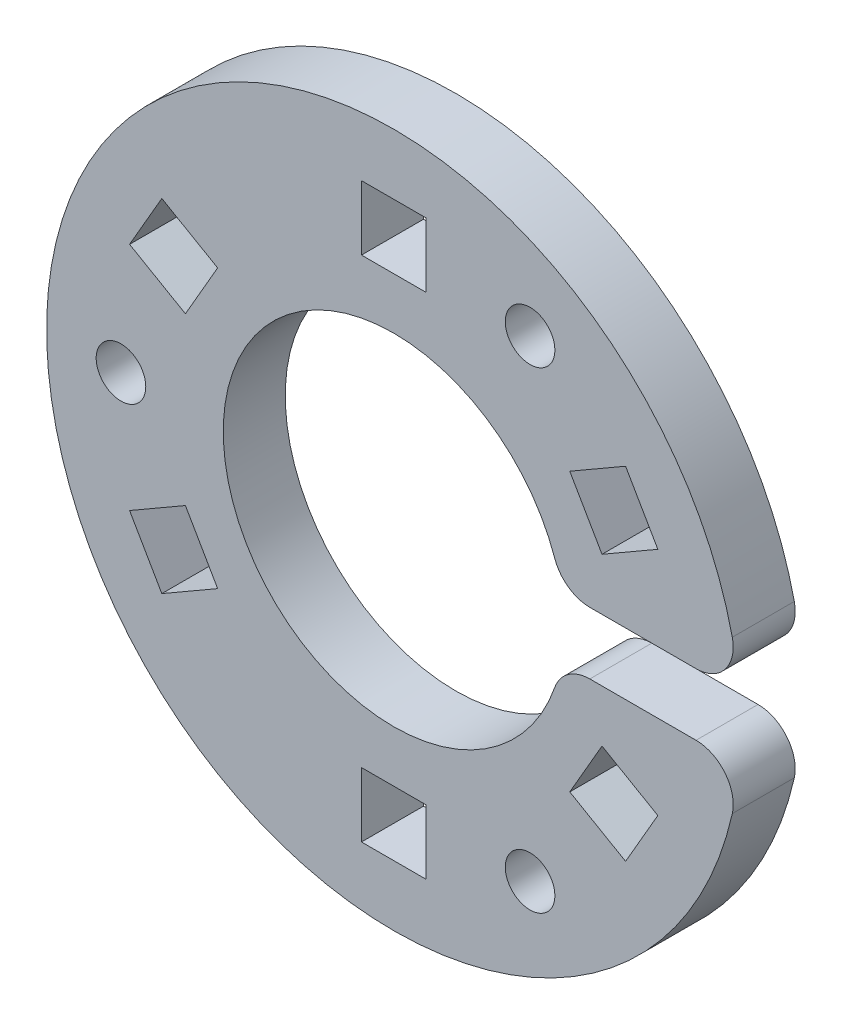
SolidWorks part; units mm, degrees
ref_plane "Front Plane" through (0, 0, 0) normal (0, 0, 1) x (1, 0, 0)
ref_plane "Top Plane" through (0, 0, 0) normal (0, 1, 0) x (1, 0, 0)
ref_plane "Right Plane" through (0, 0, 0) normal (1, 0, 0) x (0, 0, -1)
sketch "Sketch1" plane through (0, 0, 0) normal (0, 0, 1) x (1, 0, 0)
  line L0 (-26, 0) -> (26, 0) construction
  line L7 (-2.6, 23.1) -> (2.6, 23.1)
  line L8 (-2.6, 23.1) -> (-2.6, 17.9)
  line L9 (-2.6, 17.9) -> (2.6, 17.9)
  line L10 (2.6, 23.1) -> (2.6, 17.9)
  line L23 (0, 26) -> (0, -26) construction
  line L24 (21.3052, 9.2983) -> (16.8019, 6.6983)
  line L25 (14.2019, 11.2017) -> (16.8019, 6.6983)
  line L26 (18.7052, 13.8017) -> (14.2019, 11.2017)
  line L27 (18.7052, 13.8017) -> (21.3052, 9.2983)
  line L28 (18.7052, -13.8017) -> (14.2019, -11.2017)
  line L29 (16.8019, -6.6983) -> (14.2019, -11.2017)
  line L30 (21.3052, -9.2983) -> (16.8019, -6.6983)
  line L31 (21.3052, -9.2983) -> (18.7052, -13.8017)
  line L32 (-2.6, -23.1) -> (-2.6, -17.9)
  line L33 (2.6, -17.9) -> (-2.6, -17.9)
  line L34 (2.6, -23.1) -> (2.6, -17.9)
  line L35 (2.6, -23.1) -> (-2.6, -23.1)
  line L36 (-21.3052, -9.2983) -> (-16.8019, -6.6983)
  line L37 (-14.2019, -11.2017) -> (-16.8019, -6.6983)
  line L38 (-18.7052, -13.8017) -> (-14.2019, -11.2017)
  line L39 (-18.7052, -13.8017) -> (-21.3052, -9.2983)
  line L40 (-18.7052, 13.8017) -> (-14.2019, 11.2017)
  line L41 (-16.8019, 6.6983) -> (-14.2019, 11.2017)
  line L42 (-21.3052, 9.2983) -> (-16.8019, 6.6983)
  line L43 (-21.3052, 9.2983) -> (-18.7052, 13.8017)
  line L44 (27.8882, 2.5) -> (13.5208, 2.5)
  line L45 (27.8882, -2.5) -> (13.5208, -2.5)
  line L46 (27.8882, 48.3037) -> (27.8882, -48.3037) construction
  line L47 (27.8882, -48.3037) -> (-55.7763, 0) construction
  line L48 (-55.7763, 0) -> (27.8882, 48.3037) construction
  line L53 (0, 0) -> (27.8882, 48.3037) construction
  line L54 (-2.6, 20.5) -> (2.6, 20.5) construction
  circle A0 centre (0, 0) radius 13.75 construction
  arc A2 (13.5208, 2.5) -> (13.5208, -2.5) centre (0, 0) ccw
  circle A4 centre (11, 19.0526) radius 2
  circle A5 centre (11, -19.0526) radius 2
  circle A6 centre (-22, 0) radius 2
  arc A7 (27.8882, 2.5) -> (27.8882, -2.5) centre (0, 0) ccw
  point P40 (0, 0)
  point P48 (0, 0)
  point P50 (0, 0)
  point P52 (-0.4153, 0)
  dimension "D2" = 28
  dimension "D1" = 27.5
  dimension "D10" = 4
  dimension "D3" = 5.2
  dimension "D4" = 5.2
  dimension "D5" = 20.5
  dimension "D6" = 6
  dimension "D7" = 5
  dimension "D9" = 22
  dimension "D11" = 3
  dimension "D8" = 3
extrude "Boss-Extrude1" add sketch "Sketch1" along normal blind 5
fillet "Congé2" radius 3 4 edges at (13.5208, 2.5, 2.5) (13.5208, -2.5, 2.5) (27.8882, -2.5, 2.5) (27.8882, 2.5, 2.5)
